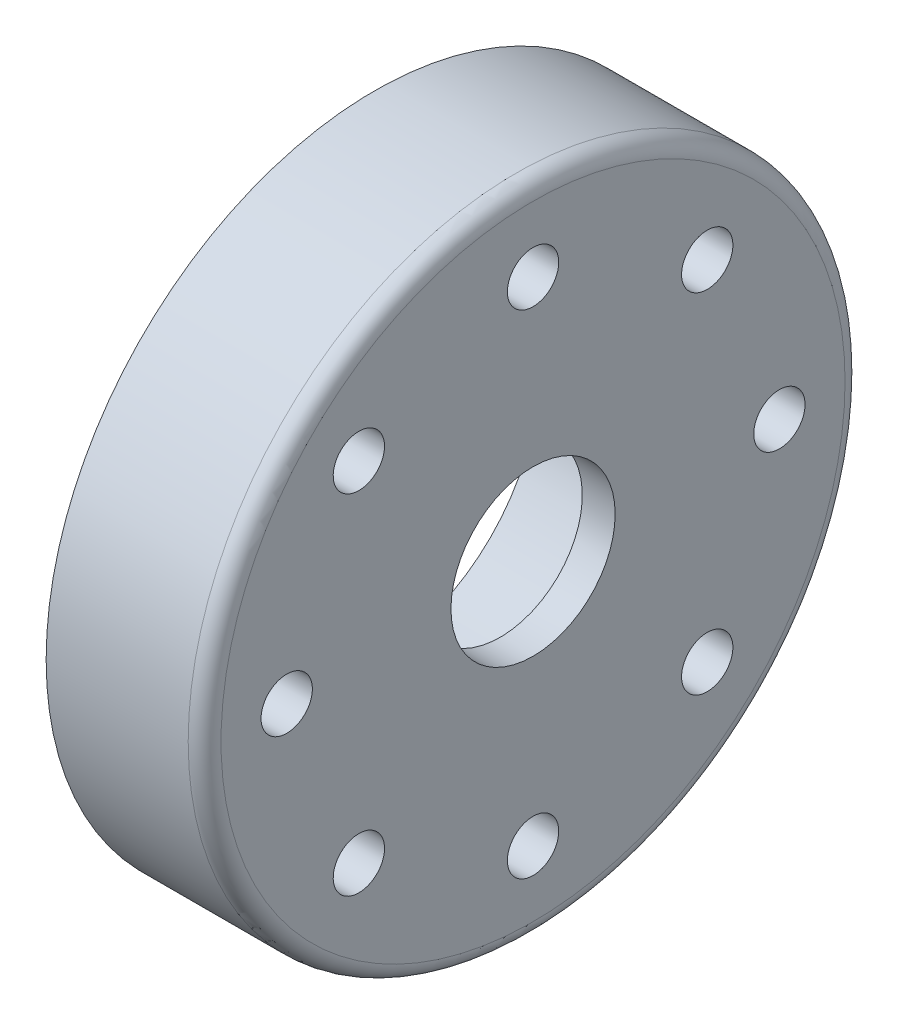
SolidWorks part; units mm, degrees
ref_plane "Front Plane" through (0, 0, 0) normal (0, 0, 1) x (1, 0, 0)
ref_plane "Top Plane" through (0, 0, 0) normal (0, 1, 0) x (1, 0, 0)
ref_plane "Right Plane" through (0, 0, 0) normal (1, 0, 0) x (0, 0, -1)
sketch "Sketch1" plane through (0, 0, 0) normal (1, 0, 0) x (0, 0, -1)
  circle A0 centre (0, 0) radius 50.8
  dimension "D1" = 101.6
extrude "Boss-Extrude1" add sketch "Sketch1" along normal blind 24.511
fillet "Fillet1" radius 2.54 1 edges at (24.511, 0, -50.8)
sketch "Sketch3" plane through (24.511, 0, 0) normal (1, 0, 0) x (0, 0, -1)
  circle A0 centre (38.1, 0) radius 3.9687
  dimension "D1" = 7.9375
  dimension "D2" = 38.1
extrude "Cut-Extrude2" cut sketch "Sketch3" against normal up to surface (24.511 mm away) up to face at (0, 0, -50.8)
pattern_circular "CirPattern1" count 8 over 360 about axis through (0, 0, 0) along (1, 0, 0) of "Cut-Extrude2"
sketch "Sketch6" plane through (0, 0, 0) normal (-1, 0, 0) x (0, 0, 1)
  circle A0 centre (0, 0) radius 25.4
  dimension "D1" = 50.8
extrude "Cut-Extrude5" cut sketch "Sketch6" against normal offset from surface (19.431 mm away) 5.08 up to face at (24.511, -42.0688, 0)
sketch "Sketch7" plane through (19.431, 0, 0) normal (-1, 0, 0) x (0, 0, 1)
  circle A0 centre (0, 0) radius 12.7
  dimension "D1" = 25.4
extrude "Cut-Extrude6" cut sketch "Sketch7" against normal up to surface (5.08 mm away) up to face at (24.511, -42.0688, 0)
